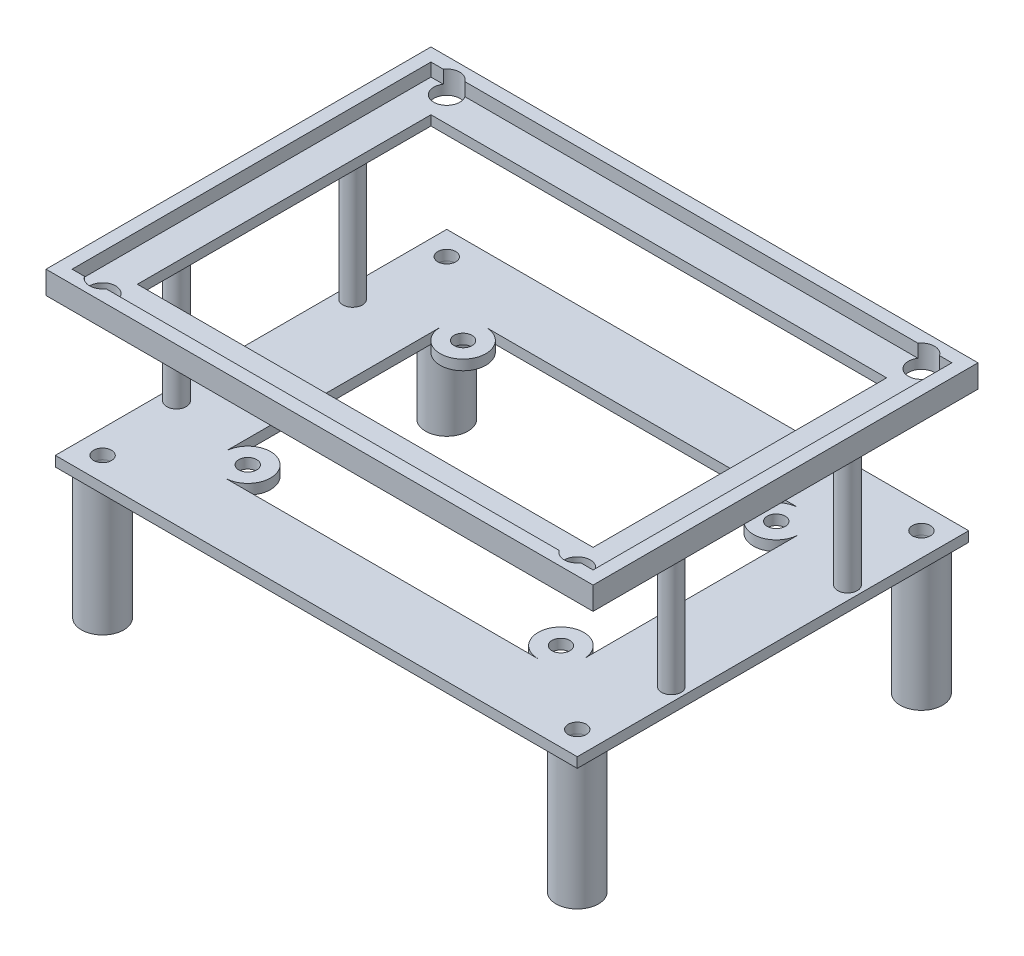
SolidWorks part; units mm, degrees
ref_plane "Front Plane" through (0, 0, 0) normal (0, 0, 1) x (1, 0, 0)
ref_plane "Top Plane" through (0, 0, 0) normal (0, 1, 0) x (1, 0, 0)
ref_plane "Right Plane" through (0, 0, 0) normal (1, 0, 0) x (0, 0, -1)
sketch "Sketch1" plane through (0, 0, 0) normal (0, 1, 0) x (1, 0, 0)
  line L0 (-36.375, 26.375) -> (-36.375, -26.375) construction
  line L1 (-40, -30) -> (40, -30)
  line L2 (-40, -30) -> (-40, 30)
  line L3 (-40, 30) -> (40, 30)
  line L4 (40, -30) -> (40, 30)
  line L5 (-40, -30) -> (40, 30) construction
  line L6 (-40, 30) -> (40, -30) construction
  line L7 (-36.375, 26.375) -> (36.375, 26.375) construction
  circle A4 centre (-36.375, 26.375) radius 1.375
  circle A5 centre (-36.375, -26.375) radius 1.375
  circle A6 centre (36.375, -26.375) radius 1.375
  circle A7 centre (36.375, 26.375) radius 1.375
  point P0 (0, 0)
  point P6 (0, 26.375)
  point P7 (-36.375, 0)
  dimension "D5" = 2.75
  dimension "D1" = 80
  dimension "D2" = 60
  dimension "D3" = 72.75
  dimension "D4" = 52.75
extrude "Boss-Extrude1" add sketch "Sketch1" along normal blind 1.55
sketch "Sketch2" plane through (0, 1.55, 0) normal (0, 1, 0) x (1, 0, 0)
  line L0 (-27.5, 20) -> (-24, 20)
  line L1 (-27.5, -20) -> (27.5, -20)
  line L2 (-27.5, -20) -> (-27.5, 20)
  line L3 (-27.5, 20) -> (27.5, 20)
  line L4 (27.5, -20) -> (27.5, 20)
  line L5 (-27.5, -20) -> (27.5, 20) construction
  line L6 (-27.5, 20) -> (27.5, -20) construction
  line L7 (0, 0) -> (-27.5, 0) construction
  line L8 (0, 0) -> (27.5, 0) construction
  line L9 (-24, -20) -> (24, -20)
  line L10 (0, 0) -> (0, 20)
  line L11 (0, 0) -> (0, -20)
  line L12 (-27.5, -16.5) -> (-27.5, 16.5)
  line L13 (-24, 20) -> (24, 20)
  line L14 (27.5, 16.5) -> (27.5, -16.5)
  line L15 (-27.5, 16.5) -> (-27.5, -16.5)
  line L16 (-24, -20) -> (24, -20)
  line L17 (27.5, -16.5) -> (27.5, 16.5)
  line L18 (-24, 20) -> (24, 20)
  circle A0 centre (-24, 16.5) radius 1.375
  circle A1 centre (24, 16.5) radius 1.375
  circle A2 centre (24, -16.5) radius 1.375
  circle A3 centre (-24, -16.5) radius 1.375
  circle A4 centre (-24, 16.5) radius 3.5
  circle A5 centre (-24, -16.5) radius 3.5
  circle A6 centre (24, -16.5) radius 3.5
  circle A7 centre (24, 16.5) radius 3.5
  point P0 (0, 0)
  dimension "D5" = 2.75
  dimension "D1" = 55
  dimension "D2" = 40
  dimension "D3" = 3.5
  dimension "D4" = 3.5
sketch "Sketch4" plane through (0, 1.55, 0) normal (0, 1, 0) x (1, 0, 0)
  line L0 (-27.5, -20) -> (27.5, -20) construction
  line L1 (-40, -30) -> (40, -30)
  line L2 (-40, -30) -> (-40, 30)
  line L3 (-40, 30) -> (40, 30)
  line L4 (40, -30) -> (40, 30)
  line L5 (-36.375, -22.75) -> (-27.5, -16.5)
  line L6 (-32.75, -26.375) -> (-24, -20)
  line L7 (0, 0) -> (0, -30) construction
  line L8 (0, 0) -> (40, 0) construction
  line L9 (36.375, -22.75) -> (27.5, -16.5)
  line L10 (32.75, -26.375) -> (24, -20)
  line L11 (32.75, 26.375) -> (24, 20)
  line L12 (36.375, 22.75) -> (27.5, 16.5)
  line L13 (-36.375, 22.75) -> (-27.5, 16.5)
  line L14 (-32.75, 26.375) -> (-24, 20)
  line L15 (-27.5, -16.5) -> (-27.5, 16.5)
  line L16 (-24, -20) -> (24, -20)
  line L17 (27.5, -16.5) -> (27.5, 16.5)
  line L18 (24, 20) -> (-24, 20)
  circle A0 centre (-24, -16.5) radius 3.5
  circle A1 centre (-36.375, -26.375) radius 3.625
  circle A2 centre (24, -16.5) radius 3.5
  circle A3 centre (36.375, -26.375) radius 3.625
  circle A4 centre (24, 16.5) radius 3.5
  circle A5 centre (36.375, 26.375) radius 3.625
  circle A6 centre (-24, 16.5) radius 3.5
  circle A7 centre (-36.375, 26.375) radius 3.625
ref_plane "Plane1" through (0, 1.55, 0) normal (0, 1, 0) x (1, 0, 0)
sketch "Sketch14" plane through (0, 1.55, 0) normal (0, 1, 0) x (1, 0, 0)
  line L0 (-27.5, -20) -> (27.5, -20) construction
  line L1 (-27.5, -20) -> (-27.5, 20) construction
  line L2 (-27.5, 20) -> (27.5, 20) construction
  line L3 (-27.5, 16.5) -> (-27.5, -16.5)
  line L4 (-24, 20) -> (24, 20)
  line L5 (27.5, 16.5) -> (27.5, -16.5)
  line L6 (-24, -20) -> (24, -20)
  arc A0 (27.5, -16.5) -> (24, -20) centre (24, -16.5) ccw
  arc A1 (-24, -20) -> (-27.5, -16.5) centre (-24, -16.5) ccw
  arc A2 (-24, 20) -> (-27.5, 16.5) centre (-24, 16.5) cw
  arc A3 (27.5, 16.5) -> (24, 20) centre (24, 16.5) cw
  circle A4 centre (-24, 16.5) radius 1.375
  circle A5 centre (24, 16.5) radius 1.375
  circle A6 centre (24, -16.5) radius 1.375
  circle A7 centre (-24, -16.5) radius 1.375
extrude "Cut-Extrude6" cut sketch "Sketch14" against normal through all contours L6 A0 L5 A3 L4 A2 L3 A1 | A6 | A5 | A7 | A4
ref_plane "Plane2" through (0, 21.55, 0) normal (0, 1, 0) x (1, 0, 0)
sketch "Sketch15" plane through (0, 21.55, 0) normal (0, 1, 0) x (1, 0, 0)
  line L0 (0, 0) -> (0, 20) construction
  line L1 (-39.925, -27.5) -> (39.925, -27.5)
  line L2 (-39.925, -27.5) -> (-39.925, 27.5)
  line L3 (-39.925, 27.5) -> (39.925, 27.5)
  line L4 (39.925, -27.5) -> (39.925, 27.5)
  line L5 (-39.925, -27.5) -> (39.925, 27.5) construction
  line L6 (-39.925, 27.5) -> (39.925, -27.5) construction
  line L7 (0, 0) -> (0, -20) construction
  line L8 (0, 0) -> (-27.5, 0) construction
  line L9 (0, 0) -> (27.5, 0) construction
  line L10 (-39.925, 27.5) -> (-34.1659, 27.5)
  line L12 (-41.925, -29.5) -> (41.925, -29.5)
  line L13 (-41.925, -29.5) -> (-41.925, 29.5)
  line L14 (-41.925, 29.5) -> (41.925, 29.5)
  line L15 (41.925, -29.5) -> (41.925, 29.5)
  line L16 (-41.925, -29.5) -> (41.925, 29.5) construction
  line L17 (-41.925, 29.5) -> (41.925, -29.5) construction
  line L18 (-34.925, -23.4071) -> (34.925, -23.4071)
  line L19 (-34.925, -23.4071) -> (-34.925, 23.4071)
  line L20 (-34.925, 23.4071) -> (34.925, 23.4071)
  line L21 (34.925, -23.4071) -> (34.925, 23.4071)
  line L22 (-34.925, -23.4071) -> (34.925, 23.4071) construction
  line L23 (-34.925, 23.4071) -> (34.925, -23.4071) construction
  point P0 (0, 0)
  dimension "D1" = 79.85
  dimension "D2" = 55
  dimension "D3" = 2
  dimension "D4" = 2
  dimension "D5" = 5
  dimension "D6" = 5
extrude "Boss-Extrude3" add sketch "Sketch15" along normal blind 3.5 separate body contours L13 L12 L15 L14 | L2 L1 L4 L3
sketch "Sketch16" plane through (0, 21.55, 0) normal (0, 1, 0) x (1, 0, 0)
  line L1 (-39.925, -27.5) -> (39.925, -27.5)
  line L2 (-39.925, -27.5) -> (-39.925, 27.5)
  line L3 (-39.925, 27.5) -> (39.925, 27.5)
  line L4 (39.925, -27.5) -> (39.925, 27.5)
  line L5 (-39.925, -27.5) -> (39.925, 27.5) construction
  line L6 (-39.925, 27.5) -> (39.925, -27.5) construction
  point P0 (0, 0)
extrude "Boss-Extrude4" add sketch "Sketch16" along normal blind 1.5
sketch "Sketch17" plane through (0, 23.05, 0) normal (0, 1, 0) x (1, 0, 0)
  line L0 (39.925, -27.5) -> (39.925, 27.5) construction
  line L1 (-34.925, -22.5) -> (34.925, -22.5)
  line L2 (-34.925, -22.5) -> (-34.925, 22.5)
  line L3 (-34.925, 22.5) -> (34.925, 22.5)
  line L4 (34.925, -22.5) -> (34.925, 22.5)
  line L5 (-34.925, -22.5) -> (34.925, 22.5) construction
  line L6 (-34.925, 22.5) -> (34.925, -22.5) construction
  line L7 (39.925, 27.5) -> (-39.925, 27.5) construction
  point P0 (0, 0)
  dimension "D1" = 5
  dimension "D2" = 5
extrude "Cut-Extrude7" cut sketch "Sketch17" against normal blind 7.5
sketch "Sketch18" plane through (0, 21.55, 0) normal (0, 1, 0) x (1, 0, 0)
  line L1 (0, 0) -> (0, -20) construction
  line L2 (0, 0) -> (27.5, 0) construction
  line L3 (-34.925, -22.5) -> (34.925, -22.5) construction
  circle A0 centre (-37.925, -13.5) radius 1.5
  circle A1 centre (37.925, -13.5) radius 1.5
  circle A2 centre (37.925, 13.5) radius 1.5
  circle A3 centre (-37.925, 13.5) radius 1.5
  dimension "D1" = 3
  dimension "D2" = 3
  dimension "D3" = 9
extrude "Boss-Extrude5" add sketch "Sketch18" against normal up to surface (20 mm away) up to face at (-24, 1.55, -15.125)
sketch "Sketch19" plane through (0, 21.55, 0) normal (0, 1, 0) x (1, 0, 0)
  line L0 (0, 0) -> (0, -20) construction
  line L1 (0, 0) -> (27.5, 0) construction
  circle A0 centre (-36.375, -26.375) radius 3.25
  circle A1 centre (36.375, -26.375) radius 3.25
  circle A2 centre (36.375, 26.375) radius 3.25
  circle A3 centre (-36.375, 26.375) radius 3.25
  circle A4 centre (-36.375, -26.375) radius 1.375
  circle A5 centre (-36.375, 26.375) radius 1.375
  circle A6 centre (36.375, -26.375) radius 1.375
  circle A7 centre (36.375, 26.375) radius 1.375
  dimension "D1" = 6.5
extrude "Boss-Extrude7" add sketch "Sketch19" against normal blind 20 from surface at -21.55 separate body starting at face at (-24, 0, -15.125)
sketch "Sketch21" plane through (0, 21.55, 0) normal (0, 1, 0) x (1, 0, 0)
  line L0 (0, 0) -> (27.5, 0) construction
  line L1 (0, 0) -> (0, 20) construction
  circle A0 centre (-36.375, 26.375) radius 2
  circle A1 centre (36.375, 26.375) radius 2
  circle A2 centre (36.375, -26.375) radius 2
  circle A3 centre (-36.375, -26.375) radius 2
  dimension "D1" = 4
extrude "Cut-Extrude11" cut sketch "Sketch21" along normal blind 32
